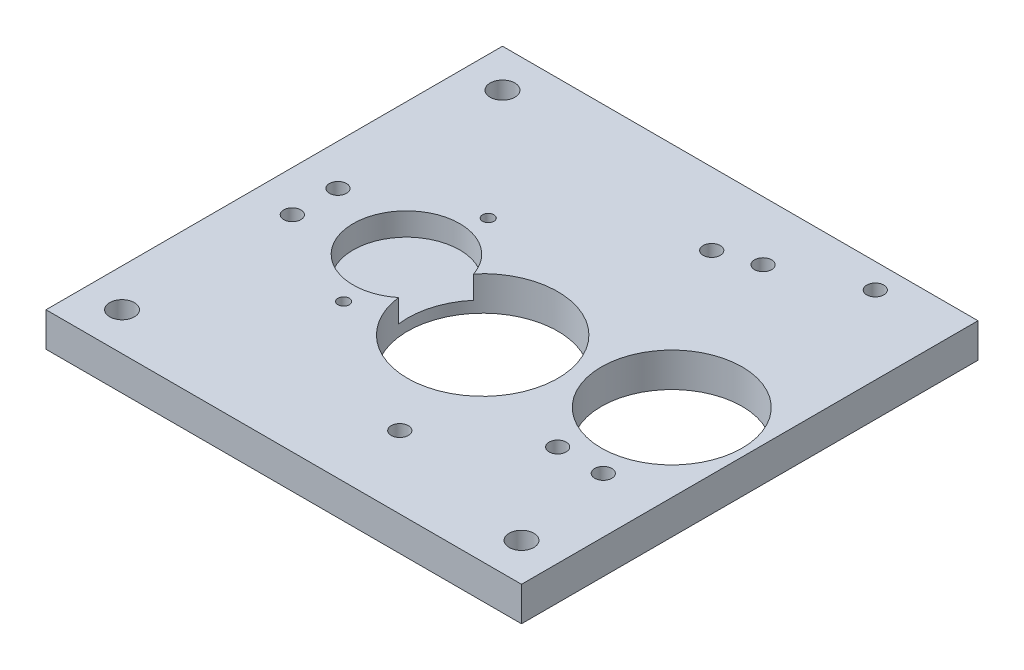
SolidWorks part; units mm, degrees
ref_plane "Front" through (0, 0, 0) normal (0, 0, 1) x (1, 0, 0)
ref_plane "Top" through (0, 0, 0) normal (0, 1, 0) x (1, 0, 0)
ref_plane "Right" through (0, 0, 0) normal (1, 0, 0) x (0, 0, -1)
sketch "Sketch1" plane through (0, 0, 0) normal (0, 1, 0) x (1, 0, 0)
  line L1 (0, 0) -> (125, 0)
  line L2 (0, 0) -> (0, 120)
  line L3 (0, 120) -> (125, 120)
  line L4 (125, 0) -> (125, 120)
  dimension "D1" = 125
  dimension "D2" = 120
extrude "Top_Base" add sketch "Sketch1" along normal blind 9
sketch "Fingers_Position" plane through (0, 9, 0) normal (0, 1, 0) x (1, 0, 0)
  line L0 (51, 79) -> (23.5, 79) construction
  line L1 (78.5, 63) -> (23.5, 63) construction
  line L2 (78.5, 63) -> (78.5, 95) construction
  line L3 (78.5, 95) -> (23.5, 95) construction
  line L4 (23.5, 63) -> (23.5, 95) construction
  line L5 (78.5, 25) -> (23.5, 25) construction
  line L6 (78.5, 25) -> (78.5, 57) construction
  line L7 (78.5, 57) -> (23.5, 57) construction
  line L8 (23.5, 25) -> (23.5, 57) construction
  line L9 (51, 95) -> (51, 63) construction
  line L10 (23.5, 41) -> (51, 41) construction
  line L11 (88.5, 109) -> (88.5, 54) construction
  line L12 (0, 120) -> (0, 0) construction
  line L13 (51, 57) -> (51, 25) construction
  line L14 (125, 60) -> (0, 60) construction
  line L15 (125, 0) -> (125, 120) construction
  line L16 (37.25, 41) -> (17.25, 41) construction
  line L17 (37.25, 41) -> (37.25, 21) construction
  line L18 (88.5, 54) -> (120.5, 54) construction
  line L19 (120.5, 54) -> (120.5, 109) construction
  line L20 (120.5, 109) -> (88.5, 109) construction
  line L21 (92.5, 69) -> (92.5, 33) construction
  line L22 (92.5, 33) -> (116.5, 33) construction
  line L23 (116.5, 33) -> (116.5, 69) construction
  line L24 (116.5, 69) -> (92.5, 69) construction
  line L25 (104.5, 109) -> (104.5, 54) construction
  line L26 (116.5, 51) -> (92.5, 51) construction
  circle A0 centre (37.25, 79) radius 20 construction
  circle A1 centre (37.25, 41) radius 20 construction
  circle A2 centre (37.25, 79) radius 20.5 construction
  circle A3 centre (37.25, 41) radius 20.5 construction
  circle A4 centre (37.25, 79) radius 19 construction
  circle A5 centre (37.25, 41) radius 19 construction
  circle A6 centre (104.5, 60) radius 9 construction
  circle A7 centre (104.5, 60) radius 17.75 construction
  point P44 (104.5, 69)
  dimension "D3" = 40
  dimension "D4" = 41
  dimension "D6" = 38
  dimension "D10" = 18
  dimension "D11" = 35.5
  dimension "D1" = 55
  dimension "D2" = 32
  dimension "D5" = 32
  dimension "D7" = 55
  dimension "D8" = 24
  dimension "D9" = 36
  dimension "D12" = 40
  dimension "D13" = 20.5
  dimension "D14" = 10
sketch "Intermediate_Gear_Position" plane through (0, 9, 0) normal (0, 1, 0) x (1, 0, 0)
  line L0 (25.75, 48) -> (25.75, 72) construction
  line L1 (25.75, 60) -> (43.75, 60) construction
  line L2 (43.75, 72) -> (43.75, 48) construction
  line L3 (10.75, 66) -> (10.75, 72) construction
  line L4 (43.75, 72) -> (7.75, 72) construction
  line L5 (92.5, 51) -> (116.5, 51) construction
  line L6 (7.75, 72) -> (7.75, 48) construction
  line L7 (43.75, 48) -> (7.75, 48) construction
  line L8 (104.5, 51) -> (104.5, 69) construction
  line L9 (125, 0) -> (125, 120) construction
  line L11 (88.5, 109) -> (120.5, 109) construction
  line L12 (120.5, 109) -> (120.5, 54) construction
  line L13 (120.5, 54) -> (88.5, 54) construction
  line L14 (88.5, 54) -> (88.5, 109) construction
  line L15 (92.5, 69) -> (92.5, 33) construction
  line L16 (92.5, 33) -> (116.5, 33) construction
  line L17 (116.5, 33) -> (116.5, 69) construction
  line L18 (116.5, 69) -> (92.5, 69) construction
  line L20 (104.5, 109) -> (104.5, 54) construction
  line L21 (10.75, 54) -> (10.75, 48) construction
  line L22 (125, 60) -> (0, 60) construction
  line L23 (78.5, 25) -> (78.5, 57) construction
  circle A0 centre (63.1461, 51.6485) radius 10 construction
  circle A3 centre (104.5, 60) radius 9 construction
  circle A4 centre (63.1461, 51.6485) radius 18 construction
  circle A6 centre (34.75, 60) radius 12.8 construction
  circle A8 centre (63.1461, 51.6485) radius 9 construction
  circle A9 centre (104.5, 60) radius 17.75 construction
  circle A10 centre (10.75, 54) radius 2 construction
  circle A12 centre (10.75, 66) radius 2 construction
  point P45 (0, 0)
  dimension "D3" = 20
  dimension "D4" = 18
  dimension "D5" = 6
  dimension "D2" = 36
  dimension "D6" = 25.6
  dimension "D17" = 35.5
  dimension "D18" = 4
  dimension "D19" = 6
  dimension "D22" = 4
  dimension "D7" = 24
  dimension "D8" = 36
  dimension "D9" = 32
  dimension "D10" = 55
  dimension "D11" = 24
  dimension "D12" = 36
  dimension "D13" = 40
  dimension "D14" = 20.5
  dimension "D15" = 34.75
  dimension "D16" = 3
  dimension "D20" = 0
  dimension "D21" = 3
sketch "Drive_Gear_Position" plane through (0, 9, 0) normal (0, 1, 0) x (1, 0, 0)
  line L21 (25.75, 48) -> (25.75, 72) construction
  circle A5 centre (34.75, 60) radius 14 construction
  circle A7 centre (34.75, 60) radius 13.5 construction
  dimension "D2" = 27
  dimension "D3" = 28
sketch "Sketch5" plane through (0, 9, 0) normal (0, 1, 0) x (1, 0, 0)
  circle A1 centre (34.75, 60) radius 14
  dimension "D1" = 28
extrude "Drive_Gear_Extrude_Cut" cut sketch "Sketch5" against normal blind 6 contours A1
sketch "Sketch8" plane through (0, 9, 0) normal (0, 1, 0) x (1, 0, 0)
  line L0 (104.5, 109) -> (104.5, 54) construction
  circle A0 centre (104.5, 60) radius 9 construction
  circle A1 centre (104.5, 60) radius 18.5
  dimension "D1" = 18
  dimension "D2" = 37
sketch "Sketch17" plane through (0, 9, 0) normal (0, 1, 0) x (1, 0, 0)
  circle A0 centre (63.1461, 51.6485) radius 19.75
  dimension "D1" = 39.5
extrude "Intermediate_Gear_Top_Part_Cut" cut sketch "Sketch17" against normal through all
extrude "Thumb_Extrude_Cut" cut sketch "Sketch8" against normal through all
sketch "Thumb_Mount_Holes" plane through (0, 9, 0) normal (0, 1, 0) x (1, 0, 0)
  line L5 (104.5, 109) -> (104.5, 113.5) construction
  line L6 (88.5, 109) -> (84, 109) construction
  line L11 (84, 109) -> (84, 104.5) construction
  line L13 (116.5, 36) -> (110.5, 36) construction
  line L15 (110.5, 36) -> (110.5, 33) construction
  line L31 (92.5, 33) -> (116.5, 33) construction
  line L32 (116.5, 33) -> (116.5, 69) construction
  line L33 (104.5, 51) -> (104.5, 33) construction
  line L34 (92.5, 51) -> (116.5, 51) construction
  circle A11 centre (104.5, 113.5) radius 2.25
  circle A12 centre (84, 104.5) radius 2.25
  circle A13 centre (110.5, 36) radius 2.25
  circle A14 centre (98.5, 36) radius 2.25
  dimension "D3" = 6
  dimension "D2" = 4.5
  dimension "D5" = 4.5
  dimension "D1" = 4.5
  dimension "D4" = 3
sketch "Connect_Holes_Position" plane through (0, 9, 0) normal (0, 1, 0) x (1, 0, 0)
  line L0 (0, 120) -> (10, 120) construction
  line L1 (125, 120) -> (0, 120) construction
  line L2 (10, 120) -> (10, 110) construction
  line L3 (125, 0) -> (115, 0) construction
  line L4 (0, 0) -> (125, 0) construction
  line L5 (115, 0) -> (115, 10) construction
  line L7 (0, 120) -> (0, 0) construction
  line L12 (0, 0) -> (0, 10) construction
  line L13 (0, 10) -> (10, 10) construction
  circle A0 centre (10, 110) radius 3.25
  circle A1 centre (115, 10) radius 3.25
  circle A4 centre (10, 10) radius 3.25
  dimension "D5" = 6.5
  dimension "D1" = 10
  dimension "D2" = 10
  dimension "D3" = 10
  dimension "D4" = 10
  dimension "D8" = 10
  dimension "D9" = 10
sketch "Fingers_Mount_Holes" plane through (0, 9, 0) normal (0, 1, 0) x (1, 0, 0)
  line L0 (78.5, 95) -> (78.5, 101) construction
  line L1 (78.5, 101) -> (74, 101) construction
  line L2 (125, 60) -> (0, 60) construction
  line L6 (7.75, 72) -> (7.75, 48) construction
  line L7 (25.75, 60) -> (7.75, 60) construction
  circle A0 centre (74, 101) radius 2.25
  circle A1 centre (74, 19) radius 2.25
  circle A2 centre (10.75, 54) radius 2.25
  circle A3 centre (10.75, 66) radius 2.25
  dimension "D3" = 4.5
  dimension "D4" = 4.5
  dimension "D1" = 6
  dimension "D2" = 4.5
sketch "Sketch26" plane through (0, 0, 0) normal (0, -1, 0) x (1, 0, 0)
  line L0 (37.25, -20.5) -> (37.25, -41) construction
  line L2 (0, -60) -> (125, -60) construction
  circle A0 centre (37.25, -41) radius 20.5 construction
  circle A1 centre (37.25, -41) radius 1.5
  circle A2 centre (37.25, -79) radius 1.5
  dimension "D2" = 3
extrude "String_Holes" cut sketch "Sketch26" against normal through all
extrude "Thumb_Mount_Holes_(M4)" cut sketch "Thumb_Mount_Holes" against normal through all
extrude "Fingers_Mount_Holes_(M4)" cut sketch "Fingers_Mount_Holes" against normal through all
extrude "Connect_Holes_(M6)" cut sketch "Connect_Holes_Position" against normal through all
sketch "Sketch27" plane through (0, 0, 0) normal (0, -1, 0) x (1, 0, 0)
  line L0 (10.75, -49) -> (6.4199, -51.5)
  line L1 (6.4199, -51.5) -> (6.4199, -56.5)
  line L2 (6.4199, -56.5) -> (10.75, -59)
  line L3 (10.75, -59) -> (15.0801, -56.5)
  line L4 (15.0801, -56.5) -> (15.0801, -51.5)
  line L5 (15.0801, -51.5) -> (10.75, -49)
  line L6 (10.75, -49) -> (10.75, -59) construction
  line L7 (10.75, -54) -> (10.75, -48) construction
  line L8 (6.4199, -51.5) -> (10.75, -54) construction
  line L9 (6.4199, -63.5) -> (6.4199, -68.5)
  line L10 (15.0801, -68.5) -> (15.0801, -63.5)
  line L11 (10.75, -61) -> (10.75, -71) construction
  line L12 (10.75, -61) -> (6.4199, -63.5)
  line L13 (6.4199, -63.5) -> (10.75, -66) construction
  line L14 (6.4199, -68.5) -> (10.75, -71)
  line L15 (15.0801, -63.5) -> (10.75, -61)
  line L16 (10.75, -71) -> (15.0801, -68.5)
  line L17 (102.8301, -38.5) -> (102.8301, -33.5)
  line L18 (98.5, -31) -> (94.1699, -33.5)
  line L19 (98.5, -31) -> (98.5, -41) construction
  line L20 (98.5, -41) -> (102.8301, -38.5)
  line L21 (94.1699, -33.5) -> (94.1699, -38.5)
  line L22 (102.8301, -33.5) -> (98.5, -31)
  line L23 (94.1699, -38.5) -> (98.5, -41)
  line L24 (94.1699, -33.5) -> (98.5, -36) construction
  line L25 (114.8301, -33.5) -> (110.5, -31)
  line L26 (106.1699, -33.5) -> (106.1699, -38.5)
  line L27 (110.5, -31) -> (106.1699, -33.5)
  line L28 (110.5, -41) -> (114.8301, -38.5)
  line L29 (106.1699, -33.5) -> (110.5, -36) construction
  line L30 (106.1699, -38.5) -> (110.5, -41)
  line L31 (114.8301, -38.5) -> (114.8301, -33.5)
  line L32 (110.5, -31) -> (110.5, -41) construction
  circle A0 centre (10.75, -66) radius 3.75 construction
  circle A1 centre (10.75, -54) radius 3.75 construction
  circle A2 centre (98.5, -36) radius 3.75 construction
  circle A3 centre (110.5, -36) radius 3.75 construction
  circle A4 centre (10.75, -66) radius 3.75 construction
  circle A5 centre (98.5, -36) radius 3.75 construction
  circle A6 centre (98.5, -36) radius 3.75 construction
  circle A7 centre (110.5, -36) radius 3.75 construction
  circle A8 centre (110.5, -36) radius 3.75 construction
  circle A9 centre (110.5, -36) radius 3.75 construction
  point P9 (110.5, -36)
  point P45 (0, 0)
  point P46 (114.8301, -38.5)
  point P47 (107.2893, -38.7451)
  point P48 (108.0971, -38.5)
  point P49 (110.5, -36)
  point P51 (91.1199, -36.2627)
  point P52 (98.5, -36)
  point P54 (10.75, -59)
  point P55 (15.0801, -56.5)
  point P56 (15.0801, -63.5)
  point P57 (10.75, -66)
  point P58 (-2.4667, -68.7043)
  point P59 (10.75, -66)
  dimension "D1" = 7.5
  dimension "D6" = 7.5
  dimension "D9" = 7.5
  dimension "D2" = 5
  dimension "D3" = 60
  dimension "D4" = 5
  dimension "D5" = 60
  dimension "D7" = 5
  dimension "D8" = 60
  dimension "D10" = 5
  dimension "D11" = 60
extrude "XL320_Nut_(M4)" cut sketch "Sketch27" against normal blind 4
